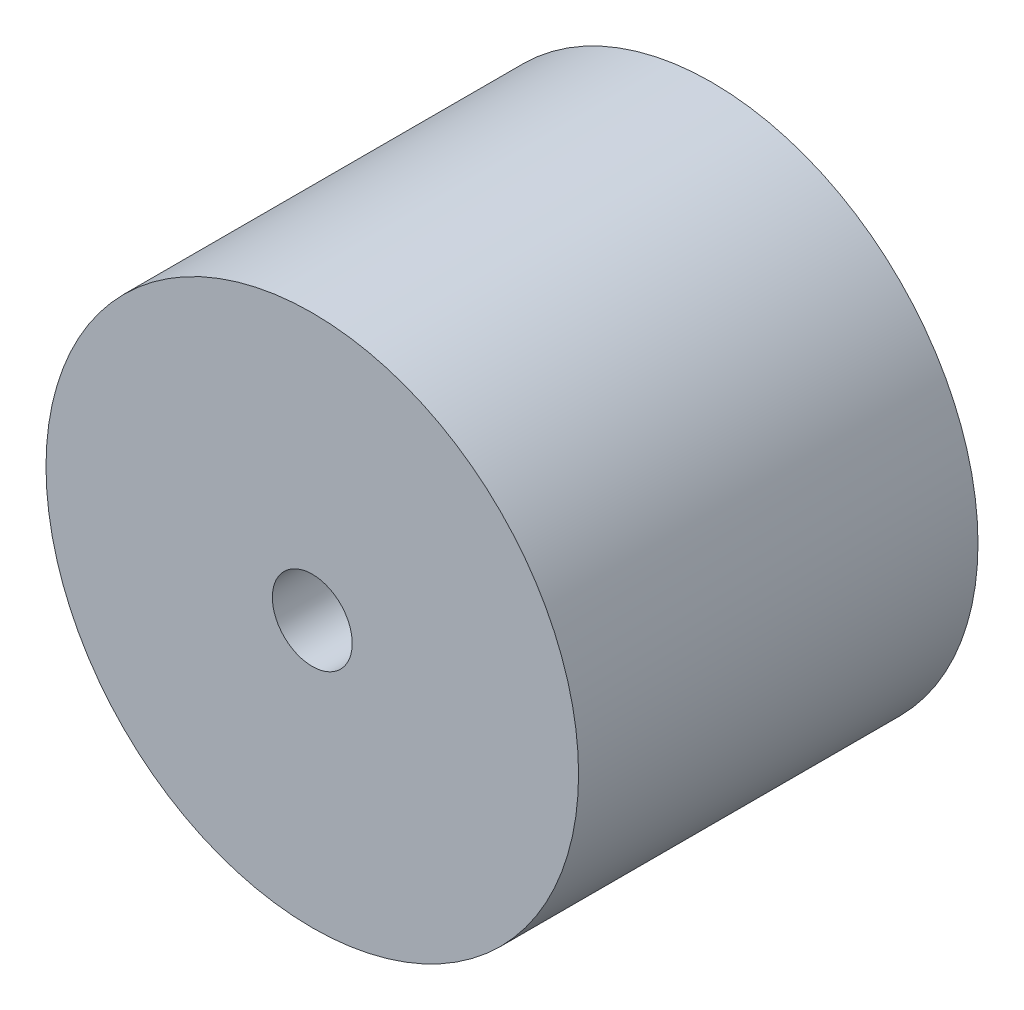
SolidWorks part; units mm, degrees
material "1060 合金"
ref_plane "前视基准面" through (0, 0, 0) normal (0, 0, 1) x (1, 0, 0)
ref_plane "上视基准面" through (0, 0, 0) normal (0, 1, 0) x (1, 0, 0)
ref_plane "右视基准面" through (0, 0, 0) normal (1, 0, 0) x (0, 0, -1)
sketch "草图1" plane through (0, 0, 0) normal (0, 0, 1) x (1, 0, 0)
  circle A0 centre (0, 0) radius 7
  circle A1 centre (0, 0) radius 20
extrude "凸台-拉伸1" add sketch "草图1" along normal blind 20
sketch "草图2" plane through (0, 0, 20) normal (0, 0, 1) x (1, 0, 0)
  circle A0 centre (0, 0) radius 20
extrude "凸台-拉伸2" add sketch "草图2" along normal blind 10
sketch "草图3" plane through (0, 0, 30) normal (0, 0, 1) x (1, 0, 0)
  circle A0 centre (0, 0) radius 3
extrude "切除-拉伸1" cut sketch "草图3" against normal blind 10 contours A0
sketch "草图4" plane through (0, 0, 0) normal (0, 0, -1) x (-1, 0, 0)
  circle A0 centre (0, 12) radius 3.5
  point P2 (0, 0)
  point P3 (0, 0)
  point P4 (0, 0)
extrude "切除-拉伸2" cut sketch "草图4" against normal blind 25 contours A0
